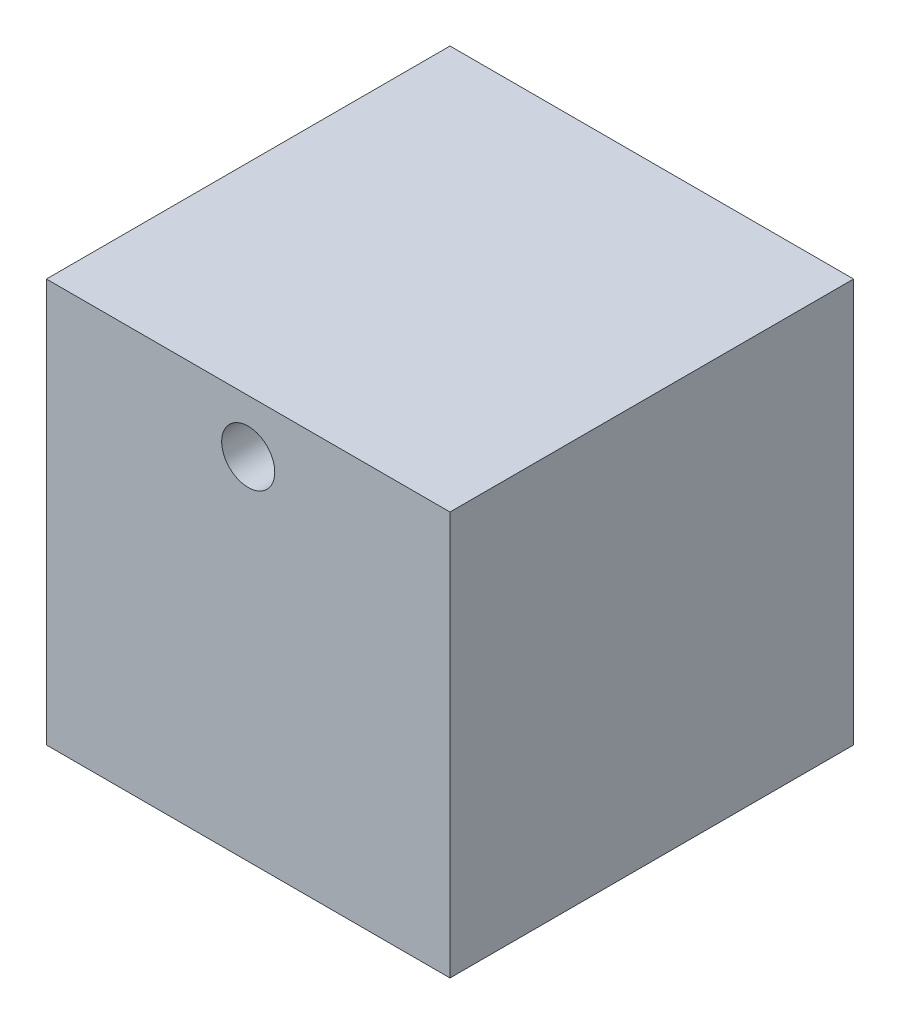
SolidWorks part; units mm, degrees
ref_plane "Front Plane" through (0, 0, 0) normal (0, 0, 1) x (1, 0, 0)
ref_plane "Top Plane" through (0, 0, 0) normal (0, 1, 0) x (1, 0, 0)
ref_plane "Right Plane" through (0, 0, 0) normal (1, 0, 0) x (0, 0, -1)
sketch "Sketch1" plane through (0, 0, 0) normal (0, 0, 1) x (1, 0, 0)
  line L1 (0, 0) -> (38, 0)
  line L2 (0, 0) -> (0, 38)
  line L3 (0, 38) -> (38, 38)
  line L4 (38, 0) -> (38, 38)
  circle A0 centre (19, 33) radius 2.5
  dimension "D5" = 5
  dimension "D1" = 38
  dimension "D2" = 38
  dimension "D3" = 5
  dimension "D4" = 19
extrude "Boss-Extrude1" add sketch "Sketch1" along normal blind 38
